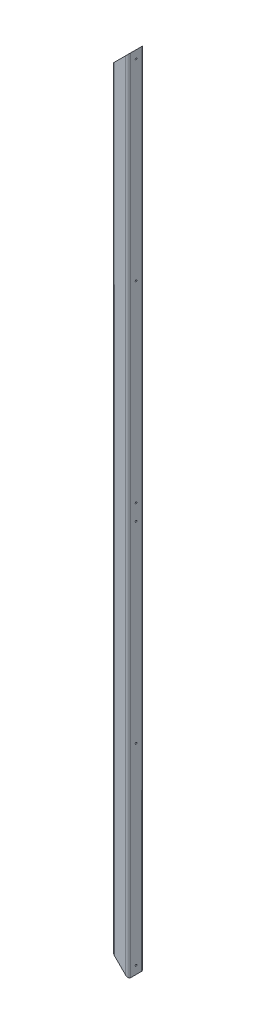
SolidWorks part; units mm, degrees
ref_plane "Front Plane" through (0, 0, 0) normal (0, 0, 1) x (1, 0, 0)
ref_plane "Top Plane" through (0, 0, 0) normal (0, 1, 0) x (1, 0, 0)
ref_plane "Right Plane" through (0, 0, 0) normal (1, 0, 0) x (0, 0, -1)
sketch "Sketch1" plane through (0, 0, 0) normal (0, 0, 1) x (1, 0, 0)
  line L0 (0, 0) -> (0, 2000)
  dimension "D1" = 2000
other "Tube (square) 40 X 40 X 3.2(1)"
ref_plane "Plane1" through (0, 0, 0) normal (0, 1, 0) x (-1, 0, 0)
sketch "Sketch15" plane through (0, 0, 0) normal (0, 1, 0) x (-1, 0, 0)
  line L0 (-13.6, -16.8) -> (13.6, -16.8)
  line L1 (-16.8, -13.6) -> (-16.8, 13.6)
  line L2 (13.6, 16.8) -> (-13.6, 16.8)
  line L3 (16.8, 13.6) -> (16.8, -13.6)
  line L4 (-13.6, -20) -> (13.6, -20)
  line L5 (-20, -13.6) -> (-20, 13.6)
  line L6 (13.6, 20) -> (-13.6, 20)
  line L7 (20, 13.6) -> (20, -13.6)
  line L8 (-20, 0) -> (-16.8, 0) construction
  line L9 (-16.8, 0) -> (16.8, 0) construction
  line L10 (16.8, 0) -> (20, 0) construction
  line L12 (0, 20) -> (0, 16.8) construction
  line L13 (0, 16.8) -> (0, -16.8) construction
  line L14 (0, -16.8) -> (0, -20) construction
  arc A0 (20, 13.6) -> (13.6, 20) centre (13.6, 13.6) ccw
  arc A1 (13.6, -20) -> (20, -13.6) centre (13.6, -13.6) ccw
  arc A2 (-20, -13.6) -> (-13.6, -20) centre (-13.6, -13.6) ccw
  arc A3 (-13.6, 20) -> (-20, 13.6) centre (-13.6, 13.6) ccw
  arc A4 (-13.6, 16.8) -> (-16.8, 13.6) centre (-13.6, 13.6) ccw
  arc A5 (16.8, 13.6) -> (13.6, 16.8) centre (13.6, 13.6) ccw
  arc A6 (13.6, -16.8) -> (16.8, -13.6) centre (13.6, -13.6) ccw
  arc A7 (-16.8, -13.6) -> (-13.6, -16.8) centre (-13.6, -13.6) ccw
  point P2 (-20, 20)
  point P33 (-20, -20)
  point P34 (20, -20)
  point P36 (20, 20)
  point P37 (0, 0)
  dimension "D1" = 6.4
  dimension "Thickness" = 3.2
  dimension "V_leg" = 40
  dimension "H_leg" = 40
ref_plane "Plane2" through (0, 0, -20) normal (0, 0, -1) x (-1, 0, 0)
sketch "Sketch13" plane through (0, 0, -20) normal (0, 0, -1) x (-1, 0, 0)
  line L0 (-20, 0) -> (20, 0) construction
  line L2 (20, 2000) -> (20, 0) construction
  line L3 (20, 2000) -> (20, 1960)
  line L4 (-13.6, 2000) -> (13.6, 2000) construction
  line L5 (-20, 2000) -> (20, 2000)
  line L9 (20, 1960) -> (-20, 2000)
  line L10 (20, 2000) -> (20, 1960)
  line L11 (20, 40) -> (20, 0)
  line L12 (-20, 0) -> (20, 40)
  dimension "D1" = 40
extrude "Cut-Extrude1" cut sketch "Sketch13" against normal through all contours L9 L3 L5 | L12 L0 L11
ref_plane "Plane3" through (20, 0, 0) normal (1, 0, 0) x (0, 0, -1)
sketch "Sketch17" plane through (20, 0, 0) normal (1, 0, 0) x (0, 0, -1)
  line L0 (-13.6, 0) -> (13.6, 0) construction
  line L1 (-13.6, 2000) -> (13.6, 2000) construction
  line L2 (-13.6, 0) -> (13.6, 0) construction
  line L3 (-13.6, 2000) -> (13.6, 2000) construction
  line L4 (-13.6, 20) -> (13.6, 20) construction
  line L5 (-13.6, 1980) -> (13.6, 1980) construction
  line L6 (-13.6, 1000) -> (13.6, 1000) construction
  line L7 (-13.6, 980) -> (13.6, 980) construction
  line L8 (-13.6, 1020) -> (13.6, 1020) construction
  line L9 (0, 20) -> (0, 980) construction
  line L10 (-13.6, 0) -> (13.6, 0)
  line L11 (13.6, 0) -> (13.6, 2000)
  line L12 (13.6, 2000) -> (-13.6, 2000)
  line L13 (-13.6, 2000) -> (-13.6, 0)
  line L14 (-13.6, 0) -> (13.6, 0) construction
  line L15 (13.6, 0) -> (13.6, 2000) construction
  line L16 (13.6, 2000) -> (-13.6, 2000) construction
  line L17 (-13.6, 2000) -> (-13.6, 0) construction
  line L18 (0, 1980) -> (0, 1020) construction
  circle A0 centre (0, 1980) radius 2
  circle A1 centre (0, 20) radius 2
  circle A2 centre (0, 1020) radius 2
  circle A3 centre (0, 980) radius 2
  circle A4 centre (0, 500) radius 2
  circle A5 centre (0, 1500) radius 2
  dimension "D2" = 20
  dimension "D3" = 0
  dimension "D6" = 4
  dimension "D1" = 20
  dimension "D4" = 20
  dimension "D5" = 20
extrude "Cut-Extrude2" cut sketch "Sketch17" against normal blind 3
